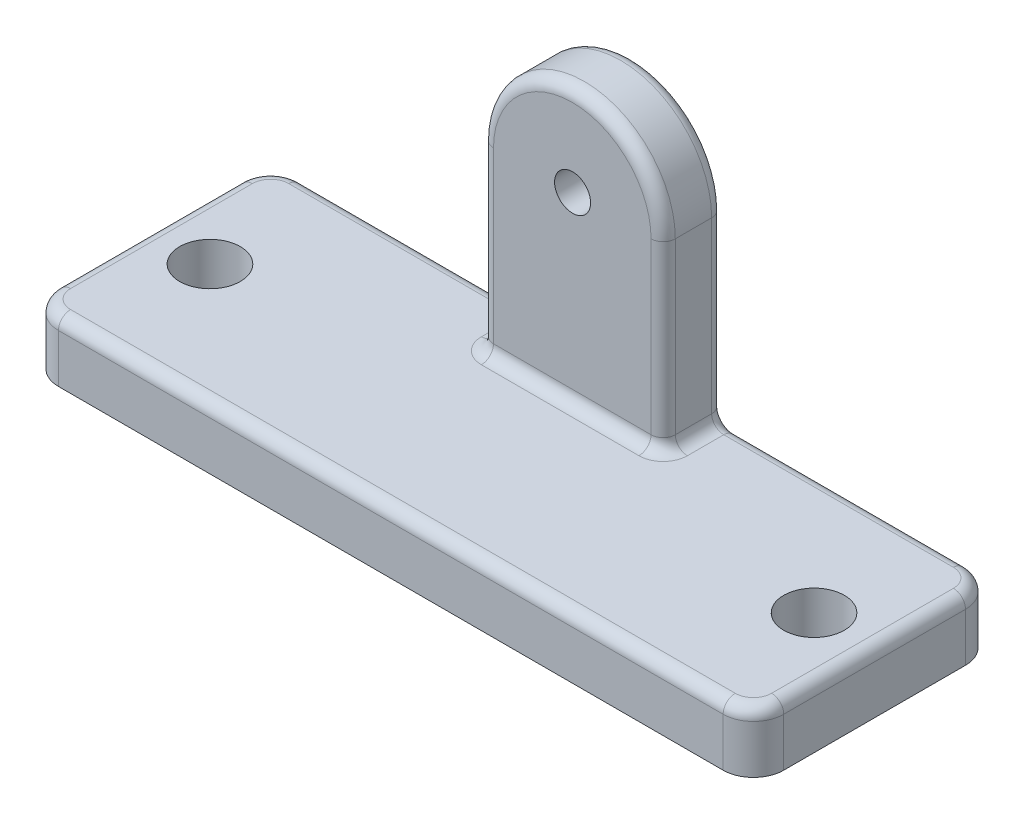
SolidWorks part; units mm, degrees
ref_plane "Alzado" through (0, 0, 0) normal (0, 0, 1) x (1, 0, 0)
ref_plane "Planta" through (0, 0, 0) normal (0, 1, 0) x (1, 0, 0)
ref_plane "Vista lateral" through (0, 0, 0) normal (1, 0, 0) x (0, 0, -1)
sketch "Croquis2" plane through (0, 0, 0) normal (0, 1, 0) x (1, 0, 0)
  line L0 (-152, 0) -> (-126.6, 0) construction
  line L1 (139.3, -50.8) -> (-139.3, -50.8)
  line L2 (152, -38.1) -> (152, 38.1)
  line L3 (139.3, 50.8) -> (-139.3, 50.8)
  line L4 (-152, -38.1) -> (-152, 38.1)
  line L5 (152, -50.8) -> (-152, 50.8) construction
  line L6 (152, 50.8) -> (-152, -50.8) construction
  line L7 (152, 0) -> (126.6, 0) construction
  arc A0 (139.3, -50.8) -> (152, -38.1) centre (139.3, -38.1) ccw
  arc A1 (152, 38.1) -> (139.3, 50.8) centre (139.3, 38.1) ccw
  arc A2 (-139.3, -50.8) -> (-152, -38.1) centre (-139.3, -38.1) cw
  arc A3 (-139.3, 50.8) -> (-152, 38.1) centre (-139.3, 38.1) ccw
  circle A4 centre (-126.6, 0) radius 12.7
  circle A5 centre (126.6, 0) radius 12.7
  point P0 (0, 0)
  dimension "D3" = 12.7
  dimension "D4" = 25.4
  dimension "D5" = 25.4
  dimension "D1" = 101.6
  dimension "D2" = 304
sketch "Croquis6" plane through (0, 0, 0) normal (0, 1, 0) x (1, 0, 0)
  circle A0 centre (-126.6, 0) radius 12.7 construction
extrude "Saliente-Extruir1" add sketch "Croquis2" along normal blind 25.4
sketch "Croquis7" plane through (0, 0, -50.8) normal (0, 0, -1) x (-1, 0, 0)
  line L0 (-38.1, 0) -> (38.1, 0) construction
  line L8 (-38.1, 0) -> (-38.1, 12.7)
  line L9 (-38.1, 12.7) -> (38.1, 12.7)
  line L10 (38.1, 0) -> (38.1, 12.7)
  line L11 (0, 0) -> (38.1, 12.7) construction
  line L12 (-38.1, 12.7) -> (0, 0) construction
  point P0 (0, 0)
  dimension "D1" = 76.2
  dimension "D2" = 12.7
extrude "Cortar-Extruir1" cut sketch "Croquis7" against normal blind 76.2 and the other way through all
sketch "Croquis9" plane through (0, 0, -50.8) normal (0, 0, -1) x (-1, 0, 0)
  line L0 (-139.3, 25.4) -> (139.3, 25.4) construction
  line L2 (-37.9687, 101.6) -> (-37.9687, 25.4)
  line L3 (-37.9687, 25.4) -> (38.2313, 25.4)
  line L4 (38.2313, 101.6) -> (38.2313, 25.4)
  arc A0 (38.2313, 101.6) -> (-37.9687, 101.6) centre (0.1313, 101.6) ccw
  point P0 (0, 63.5)
  point P10 (-208.2873, 117.6831)
  point P11 (38.2313, 101.6)
  dimension "D3" = 76.2
  dimension "D2" = 76.2
extrude "Saliente-Extruir2" add sketch "Croquis9" against normal blind 25.4
hole_wizard "Refrentado para tornillo con cabeza troncocónica de 9/162" positions "Croquis12" profile "Croquis11" counterbore size "9/16" standard "Ansi Inch" end condition through all
sketch "Croquis12" plane through (0, 0, -50.8) normal (0, 0, -1) x (-1, 0, 0)
  point P0 (0, 101.9653)
sketch "Croquis11" plane through (0, 101.9653, -50.8) normal (1, 0, 0) x (0, 1, 0)
  line L0 (0, 0) -> (0, 101.6)
  line L1 (0, 101.6) -> (7.54, 101.6)
  line L3 (7.54, 101.6) -> (7.54, 9.9314)
  line L4 (13.6919, 9.9314) -> (7.54, 9.9314)
  line L5 (13.6919, 9.9314) -> (13.6919, 0.635)
  line L6 (13.6919, 0.635) -> (14.3269, 0)
  line L7 (14.3269, 0) -> (0, 0)
  line L8 (-13.6919, 0.635) -> (-14.3269, 0) construction
  line L11 (0, -6.35) -> (0, 107.95) construction
  dimension "Diámetro de taladro hasta el siguiente" = 15.08
  dimension "Profundidad de taladro hasta el siguiente" = 101.6
  dimension "Diámetro de refrentado" = 27.3837
  dimension "Profundidad de refrentado" = 9.9314
  dimension "Diámetro de avellanado cercano" = 28.6537
  dimension "Ángulo de avellanado cercano" = 90
fillet "Redondeo1" radius 5.08 18 edges at (-0.1313, 25.4, -25.4) (-88.7657, 25.4, -50.8) (-148.2803, 25.4, -47.0803) (-152, 25.4, 0) (-148.2803, 25.4, 47.0803) (0, 25.4, 50.8) (148.2803, 25.4, 47.0803) (152, 25.4, 0) (148.2803, 25.4, -47.0803) (-0.1313, 139.7, -50.8) (-38.2313, 63.5, -25.4) (37.9687, 63.5, -25.4) (88.6343, 25.4, -50.8) (37.9687, 25.4, -38.1) (-38.2313, 25.4, -38.1) (37.9687, 63.5, -50.8) (-38.2313, 63.5, -50.8) (-0.1313, 139.7, -25.4)
